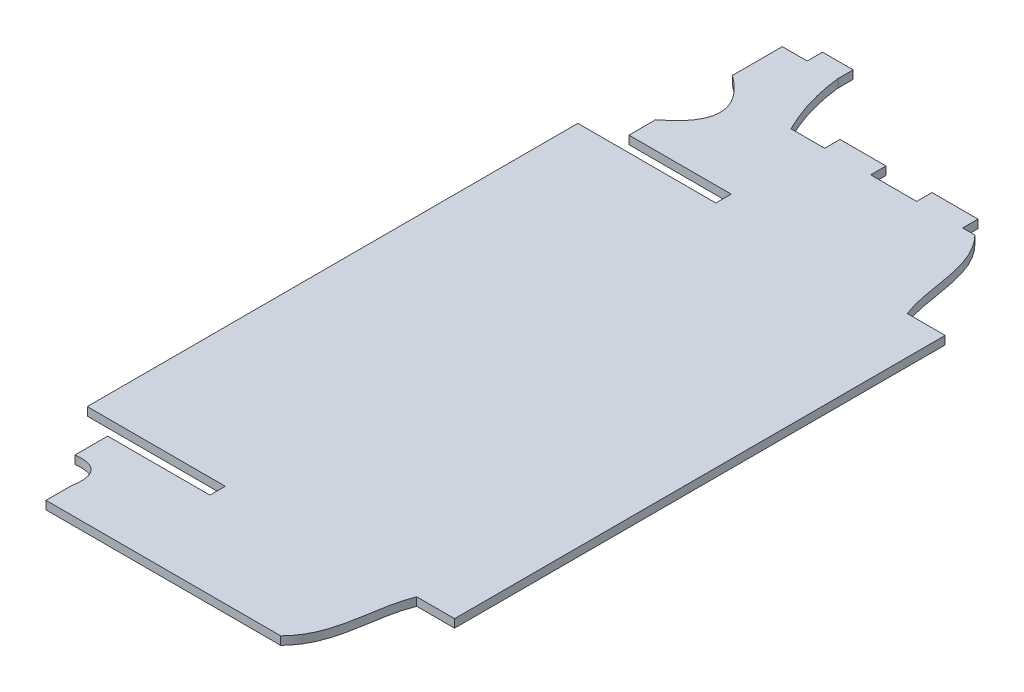
SolidWorks part; units mm, degrees
ref_plane "Front Plane" through (0, 0, 0) normal (0, 0, 1) x (1, 0, 0)
ref_plane "Top Plane" through (0, 0, 0) normal (0, 1, 0) x (1, 0, 0)
ref_plane "Right Plane" through (0, 0, 0) normal (1, 0, 0) x (0, 0, -1)
sketch "Sketch1" plane through (0, 0, 0) normal (0, 0, 1) x (1, 0, 0)
  line L0 (-69.6894, -130) -> (-74.7353, -130) construction
  line L1 (-69.6108, -131.35) -> (-189.395, -131.35)
  line L2 (-69.6108, -131.35) -> (-69.6108, -128.65)
  line L3 (-69.6108, -128.65) -> (-189.395, -128.65)
  line L4 (-189.395, -131.35) -> (-189.395, -128.65)
  line L5 (-69.6108, -130) -> (-69.6108, -129.7588) construction
  line L6 (-87.395, -128.411) -> (-87.395, -126.7202) construction
  point P5 (-69.6108, -130)
  dimension "D1" = 2.7
  dimension "D2" = 102
extrude "Boss-Extrude1" add sketch "Sketch1" along normal mid plane 160
sketch "Sketch2" plane through (0, -128.65, 0) normal (0, 1, 0) x (1, 0, 0)
  line L0 (-189.395, -80) -> (-69.6108, -80) construction
  line L1 (-69.6108, -80) -> (-189.395, -80) construction
  line L2 (-93.1058, -113.2) -> (-169.6481, -113.2)
  line L4 (-1148.0116, 113.2) -> (-189.395, 113.2) construction
  line L5 (-177.7318, -85) -> (-177.7318, -95.6465)
  line L6 (-177.7318, -77.7202) -> (-81.9487, -77.7202)
  line L7 (-81.9487, -77.7202) -> (-81.9487, -80)
  line L8 (-87.395, 0) -> (-81.9487, 0) construction
  line L9 (-177.7318, 77.7202) -> (-81.9487, 77.7202)
  line L11 (-93.1058, 113.2) -> (-97.1058, 113.2)
  line L12 (-81.9487, 77.7202) -> (-81.9487, 80)
  line L13 (-127.1058, 113.2) -> (-112.1058, 113.2) construction
  line L15 (-97.1058, 113.2) -> (-97.1058, 118.2)
  line L16 (-97.1058, 118.2) -> (-112.1058, 118.2)
  line L17 (-112.1058, 113.2) -> (-112.1058, 118.2)
  line L19 (-127.1058, 113.2) -> (-127.1058, 118.2)
  line L20 (-127.1058, 118.2) -> (-142.1058, 118.2)
  line L21 (-142.1058, 113.2) -> (-142.1058, 118.2)
  line L22 (-142.1058, 113.2) -> (-153.1058, 113.2)
  line L23 (-112.1058, 113.2) -> (-127.1058, 113.2)
  line L24 (-97.1058, 113.2) -> (892.1753, 113.2) construction
  line L27 (-169.6202, 135) -> (-177.7318, 135)
  line L29 (-153.1058, 113.2) -> (-142.1058, 113.2) construction
  line L32 (-159.6202, 135) -> (-159.6202, 140)
  line L33 (-159.6202, 140) -> (-169.6202, 140)
  line L34 (-169.6202, 135) -> (-169.6202, 140)
  line L39 (-177.7318, -77.7202) -> (-177.7318, -80)
  line L40 (-177.7318, 85) -> (-144.395, 85)
  line L42 (-177.7318, 80) -> (-144.395, 80)
  line L43 (-144.395, 85) -> (-144.395, 80)
  line L44 (-69.6108, 80) -> (-189.395, 80) construction
  line L46 (-144.395, -85) -> (-144.395, -80)
  line L48 (-177.7318, -85) -> (-144.395, -85)
  line L52 (-169.6481, -105.0877) -> (-169.6481, -113.2)
  line L59 (-177.7318, 80) -> (-177.7318, 77.7202)
  line L60 (-177.7318, 135) -> (-177.7318, 85)
  line L62 (-177.7318, -80) -> (-144.395, -80)
  spline S0 degree 3 poles (-81.9487, -80) (-86.3428, -90.9894) (-84.0042, -103.8881) (-93.1058, -113.2) knots 0 0 0 0 1 1 1 1
  spline S1 degree 3 poles (-81.9487, 80) (-86.3428, 90.9894) (-84.0042, 103.8881) (-93.1058, 113.2) knots 0 0 0 0 1 1 1 1
  spline S2 degree 2 poles (-153.1058, 113.2) (-158.3104, 123.5197) (-159.6202, 135) knots 0 0 0 1 1 1
  spline S3 degree 2 poles (-177.7318, 93.703) (-160.8365, 106.3956) (-177.7318, 118.7285) knots 0 0 0 1 1 1
  spline S4 degree 2 poles (-169.6481, -105.0877) (-167.7602, -94.5142) (-177.7318, -95.6465) knots 0 0 0 1 1 1
  dimension "D1" = 15
  dimension "D2" = 15
  dimension "D3" = 15
  dimension "D4" = 5
  dimension "D5" = 10
  dimension "D7" = 5
extrude "Boss-Extrude2" add sketch "Sketch2" against normal blind 2.7
